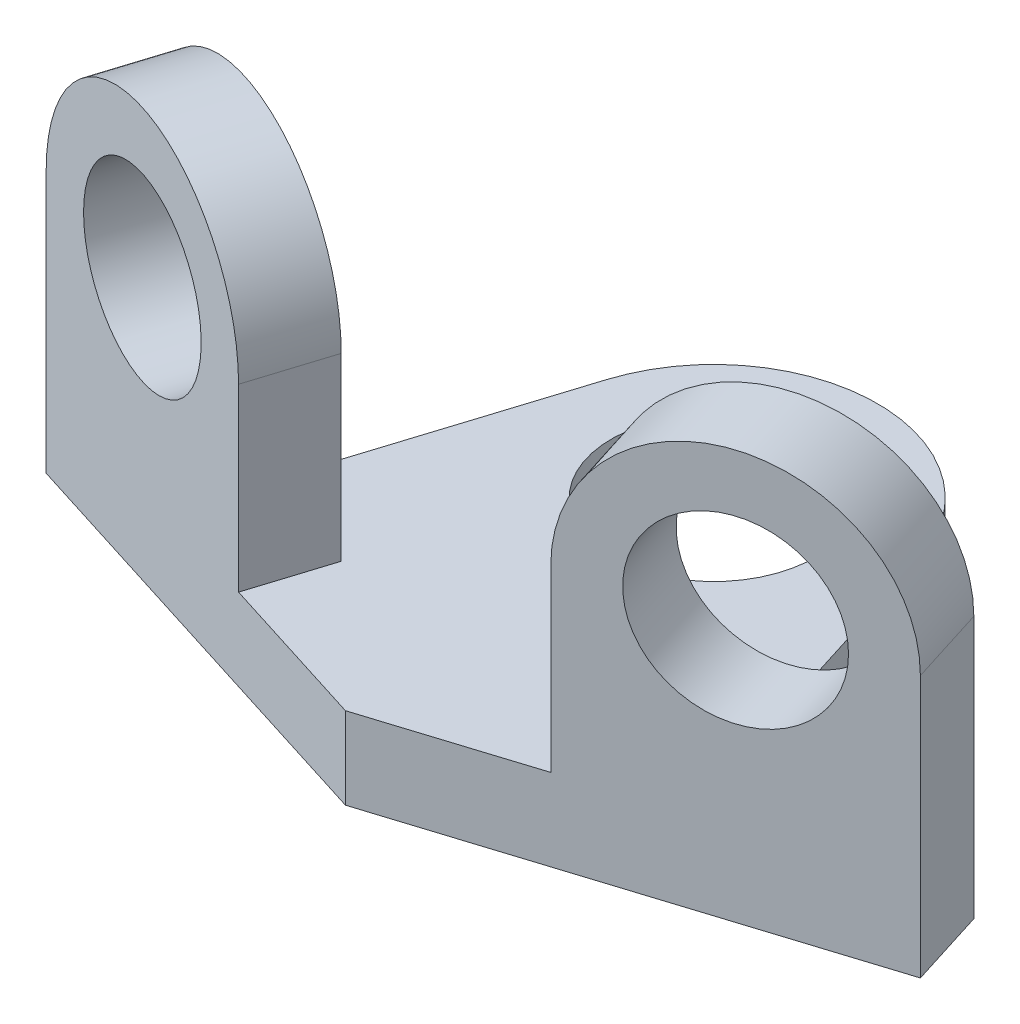
SolidWorks part; units mm, degrees
ref_plane "Front Plane" through (0, 0, 0) normal (0, 0, 1) x (1, 0, 0)
ref_plane "Top Plane" through (0, 0, 0) normal (0, 1, 0) x (1, 0, 0)
ref_plane "Right Plane" through (0, 0, 0) normal (1, 0, 0) x (0, 0, -1)
sketch "Sketch3" plane through (0, 0, 0) normal (0, 1, 0) x (1, 0, 0)
  line L0 (-19.0743, 51.0141) -> (-31.9798, 10.0832)
  line L2 (0, -55) -> (0, 55) construction
  line L3 (19.0743, 51.0141) -> (31.9798, 10.0832)
  line L4 (0, 0) -> (31.9798, 10.0832)
  line L5 (0, 0) -> (-31.9798, 10.0832)
  circle A0 centre (0, 45) radius 12.5
  arc A1 (19.0743, 51.0141) -> (-19.0743, 51.0141) centre (0, 45) ccw
  dimension "D2" = 25
  dimension "D4" = 40
  dimension "D1" = 35
  dimension "D3" = 45
  dimension "D5" = 90
extrude "Boss-Extrude1" add sketch "Sketch3" along normal blind 10
sketch "Sketch6" plane through (0, 0, 0) normal (0.3007, 0, 0.9537) x (0.9537, 0, -0.3007)
  line L0 (20, 32) -> (20, 0)
  line L1 (55, 0) -> (-55, 0) construction
  line L2 (56, 32) -> (56, 0)
  line L3 (20, 0) -> (56, 0)
  arc A0 (56, 32) -> (20, 32) centre (38, 32) ccw
  circle A1 centre (38, 32) radius 11
  dimension "D1" = 36
  dimension "D2" = 22
  dimension "D3" = 20
  dimension "D4" = 32
extrude "Boss-Extrude2" add sketch "Sketch6" against normal blind 10
mirror "Mirror2" about plane through (0, 0, 0) normal (1, 0, 0) of "Boss-Extrude2"
